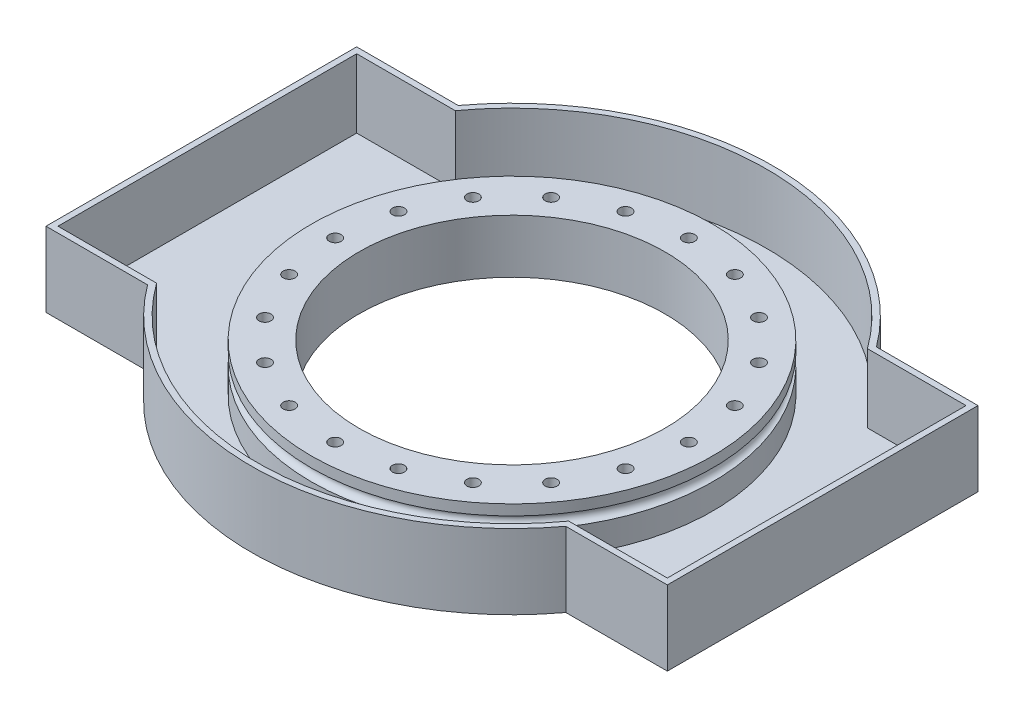
SolidWorks part; units mm, degrees
ref_plane "Plan de face" through (0, 0, 0) normal (0, 0, 1) x (1, 0, 0)
ref_plane "Plan de dessus" through (0, 0, 0) normal (0, 1, 0) x (1, 0, 0)
ref_plane "Plan de droite" through (0, 0, 0) normal (1, 0, 0) x (0, 0, -1)
sketch "Esquisse1" plane through (0, 0, 0) normal (0, 0, 1) x (1, 0, 0)
  line L0 (-256, 27.4194) -> (-256, -16.0215) construction
  line L1 (0, 0) -> (80, 0)
  line L2 (0, 0) -> (0, 90)
  line L3 (0, 90) -> (80, 90)
  line L4 (80, 0) -> (80, 52.5)
  line L5 (80, 72.5) -> (80, 90)
  arc A0 (80, 72.5) -> (80, 52.5) centre (80, 62.5) ccw
  dimension "D4" = 10
  dimension "D1" = 80
  dimension "D2" = 90
  dimension "D3" = 62.5
  dimension "D5" = 256
revolve "Révolution1" add sketch "Esquisse1" angle 360 about L0
sketch "Esquisse2" plane through (0, 0, 0) normal (0, -1, 0) x (1, 0, 0)
  line L0 (0, 0) -> (35.0097, 0) construction
  line L1 (0, 0) -> (80, 0) construction
  circle A0 centre (-256, 0) radius 336 construction
  circle A1 centre (40, 0) radius 10
  dimension "D2" = 20
  dimension "D1" = 40
extrude "Enlèv. mat.-Extru.1" cut sketch "Esquisse2" against normal through all
pattern_circular "Répétition circulaire1" count 20 over 360 about axis through (-256, 0, 0) along (0, 1, 0) of "Enlèv. mat.-Extru.1"
sketch "Esquisse5" plane through (0, 0, 0) normal (0, -1, 0) x (1, 0, 0)
  circle A1 centre (-256, 0) radius 336 construction
  circle A2 centre (-256, 0) radius 436
  circle A3 centre (-256, 0) radius 436
  circle A4 centre (-256, 0) radius 336
  dimension "D1" = 100
extrude "Boss.-Extru.1" add sketch "Esquisse5" against normal blind 10
sketch "Esquisse6" plane through (0, 10, 0) normal (0, 1, 0) x (1, 0, 0)
  circle A1 centre (-256, 0) radius 436 construction
  circle A2 centre (-256, 0) radius 426
  circle A3 centre (-256, 0) radius 426
  circle A4 centre (-256, 0) radius 436
  dimension "D1" = 10
extrude "Boss.-Extru.2" add sketch "Esquisse6" along normal blind 115
sketch "Esquisse7" plane through (0, 0, 0) normal (0, -1, 0) x (1, 0, 0)
  line L1 (93.9943, 260) -> (263.9943, 260)
  line L3 (93.9943, -260) -> (263.9943, -260)
  line L4 (263.9943, 260) -> (263.9943, -260)
  circle A0 centre (-256, 0) radius 436 construction
  arc A1 (93.9943, -260) -> (93.9943, 260) centre (-256, 0) ccw
  point P6 (0, 0)
  dimension "D1" = 520
  dimension "D2" = 170
extrude "Boss.-Extru.3" add sketch "Esquisse7" against normal blind 10
sketch "Esquisse8" plane through (0, 10, 0) normal (0, 1, 0) x (1, 0, 0)
  line L3 (253.9943, 250) -> (101.2058, 250)
  line L4 (253.9943, -250) -> (101.2058, -250)
  line L5 (113.3454, 250) -> (101.2058, 250)
  line L6 (113.3454, -250) -> (253.9943, -250)
  line L7 (253.9943, -250) -> (253.9943, 250)
  line L8 (253.9943, 250) -> (113.3454, 250)
  line L9 (113.3454, -250) -> (253.9943, -250)
  line L10 (253.9943, -250) -> (253.9943, 250)
  line L11 (253.9943, 250) -> (113.3454, 250)
  line L12 (113.3454, -250) -> (101.2058, -250)
  line L13 (263.9943, -260) -> (93.9943, -260) construction
  line L14 (263.9943, 260) -> (263.9943, -260) construction
  line L15 (93.9943, 260) -> (263.9943, 260) construction
  line L16 (263.9943, -260) -> (93.9943, -260)
  line L17 (263.9943, 260) -> (263.9943, -260)
  line L18 (93.9943, 260) -> (263.9943, 260)
  arc A1 (93.9943, -260) -> (93.9943, 260) centre (-256, 0) ccw construction
  arc A2 (113.3454, -250) -> (113.3454, 250) centre (-256, 0) ccw
  arc A4 (101.2058, 250) -> (93.9943, 260) centre (-256, 0) ccw
  arc A5 (93.9943, -260) -> (101.2058, -250) centre (-256, 0) ccw
  arc M9 (93.9943, 260) -> (93.9943, -260) centre (-256, 0) cw
  line M10 (93.9943, -260) -> (263.9943, -260)
  line M11 (263.9943, -260) -> (263.9943, 260)
  line M12 (263.9943, 260) -> (93.9943, 260)
  dimension "D1" = 10
extrude "Boss.-Extru.4" add sketch "Esquisse8" along normal blind 115 contours L10 L4 L3 M9 M10 M11 M12
sketch "Esquisse9" plane through (0, 125, 0) normal (0, 1, 0) x (1, 0, 0)
  line L0 (101.2058, -250) -> (88.929, -250)
  line L1 (101.2058, 250) -> (88.929, 250)
  line L5 (101.2058, -250) -> (253.9943, -250)
  line L6 (253.9943, 250) -> (101.2058, 250)
  line L7 (253.9943, -250) -> (253.9943, 250)
  circle A0 centre (-256, 0) radius 426 construction
  circle A1 centre (-256, 0) radius 426 construction
  arc A2 (88.929, -250) -> (88.929, 250) centre (-256, 0) ccw
  arc A3 (101.2058, -250) -> (101.2058, 250) centre (-256, 0) ccw
  arc A4 (101.2058, -250) -> (101.2058, 250) centre (-256, 0) ccw
  dimension "D1" = 0
extrude "Enlèv. mat.-Extru.3" cut sketch "Esquisse9" against normal blind 115
pattern_circular "Répétition circulaire6" count 2 over 360 of "Enlèv. mat.-Extru.3", "Boss.-Extru.4", "Boss.-Extru.3"
